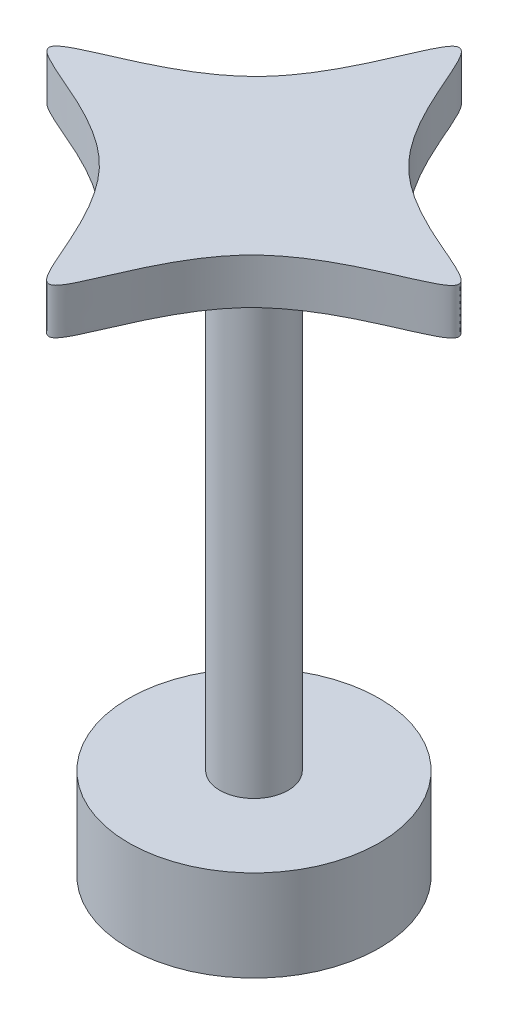
SolidWorks part; units mm, degrees
material "BUTYL"
ref_plane "Front Plane" through (0, 0, 0) normal (0, 0, 1) x (1, 0, 0)
ref_plane "Top Plane" through (0, 0, 0) normal (0, 1, 0) x (1, 0, 0)
ref_plane "Right Plane" through (0, 0, 0) normal (1, 0, 0) x (0, 0, -1)
sketch "Sketch1" plane through (0, 0, 0) normal (0, 1, 0) x (1, 0, 0)
  circle A0 centre (0, 0) radius 17.4625
extrude "Boss-Extrude1" add sketch "Sketch1" along normal blind 12.7
sketch "Sketch2" plane through (0, 12.7, 0) normal (0, 1, 0) x (1, 0, 0)
  circle A0 centre (0, 0) radius 4.7625
extrude "Boss-Extrude2" add sketch "Sketch2" along normal blind 66.675
sketch "Sketch3" plane through (0, 79.375, 0) normal (0, 1, 0) x (1, 0, 0)
  line L0 (0, 0) -> (0, 28.575) construction
  line L1 (0, 0) -> (28.575, 0) construction
  line L2 (0, 0) -> (0, -28.575) construction
  line L3 (0, 0) -> (-28.575, 0) construction
  line L4 (0, 0) -> (10.9894, 10.5589) construction
  line L5 (0, 0) -> (10.5589, -10.9894) construction
  line L6 (0, 0) -> (-10.9894, -10.5589) construction
  line L7 (0, 0) -> (-10.5589, 10.9894) construction
  spline S0 degree 3 poles (-39.7516, 0.0341) (-6.1439, 6.302) (0.0341, 39.7516) (6.302, 6.1439) (39.7516, -0.0341) (6.1439, -6.302) (-0.0341, -39.7516) (-6.302, -6.1439) (-39.7516, 0.0341) (-6.1439, 6.302) (0.0341, 39.7516) knots -0.376776 -0.25 -0.126776 0 0.123224 0.25 0.373224 0.5 0.623224 0.75 0.873224 1 1.123224 1.25 1.373224 only from (-10.5589, 10.9894) to (-10.5589, 10.9894)
extrude "Boss-Extrude3" add sketch "Sketch3" along normal blind 6.35
